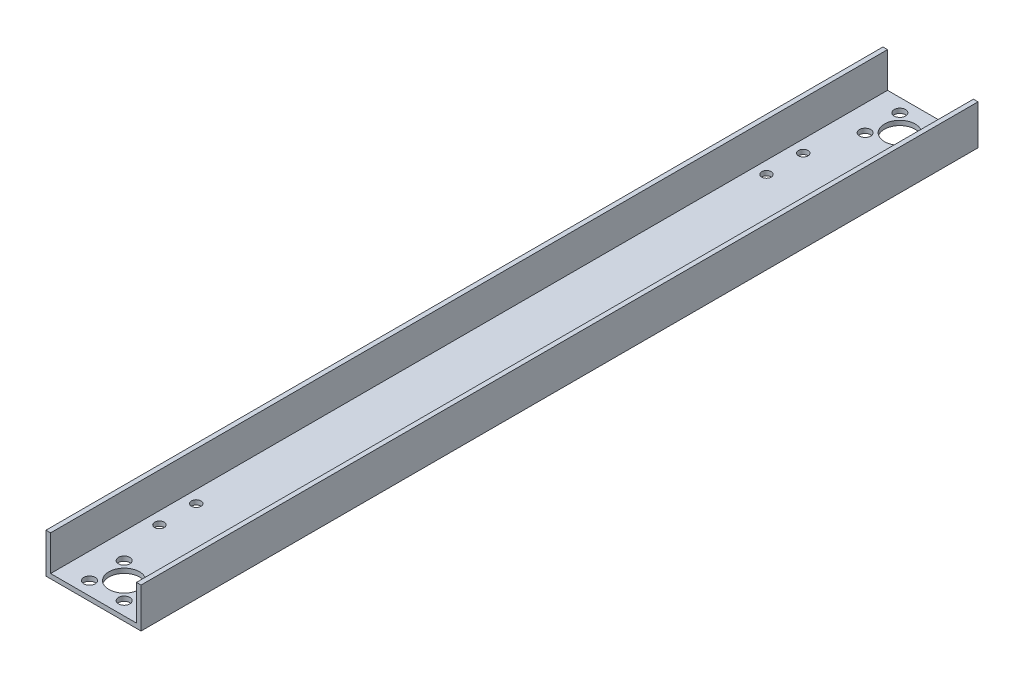
SolidWorks part; units mm, degrees
ref_plane "Front Plane" through (0, 0, 0) normal (0, 0, 1) x (1, 0, 0)
ref_plane "Top Plane" through (0, 0, 0) normal (0, 1, 0) x (1, 0, 0)
ref_plane "Right Plane" through (0, 0, 0) normal (1, 0, 0) x (0, 0, -1)
sketch "Sketch1" plane through (0, 0, 0) normal (0, 0, 1) x (1, 0, 0)
  line L0 (14, 6.5) -> (15.5, 6.5)
  line L1 (-15.5, 6.5) -> (-14, 6.5)
  line L2 (-15.5, 6.5) -> (-15.5, -6.5)
  line L3 (-15.5, -6.5) -> (15.5, -6.5)
  line L4 (15.5, 6.5) -> (15.5, -6.5)
  line L5 (-15.5, 6.5) -> (15.5, -6.5) construction
  line L6 (-15.5, -6.5) -> (15.5, 6.5) construction
  line L8 (-14, 6.5) -> (-14, -5)
  line L9 (-14, -5) -> (14, -5)
  line L10 (14, 6.5) -> (14, -5)
  point P0 (0, 0)
  dimension "D1" = 13
  dimension "D2" = 31
  dimension "D3" = 1.5
  dimension "D4" = 1.5
extrude "Boss-Extrude1" add sketch "Sketch1" along normal blind 273
sketch "Sketch3" plane through (0, -5, 0) normal (0, 1, 0) x (1, 0, 0)
  line L0 (0, 0) -> (0, -273) construction
  line L1 (14, -273) -> (-14, -273) construction
  line L3 (0, -136.5) -> (15.5, -136.5) construction
  line L4 (5.6569, -257.3431) -> (-5.6569, -268.6569) construction
  line L5 (0, -263) -> (0.7501, -263) construction
  line L6 (5.6569, -268.6569) -> (-5.6569, -257.3431) construction
  line L7 (15.5, -273) -> (15.5, 0) construction
  line L8 (5.6569, -4.3431) -> (-5.6569, -15.6569) construction
  line L9 (0, -10) -> (0.7501, -10) construction
  line L10 (5.6569, -15.6569) -> (-5.6569, -4.3431) construction
  circle A0 centre (-5.6569, -4.3431) radius 1.85
  circle A1 centre (0, -263) radius 5
  circle A2 centre (-5.6569, -257.3431) radius 1.85
  circle A3 centre (5.6569, -257.3431) radius 1.85
  circle A4 centre (5.6569, -268.6569) radius 1.85
  circle A5 centre (-5.6569, -268.6569) radius 1.85
  circle A6 centre (5.6569, -4.3431) radius 1.85
  circle A7 centre (5.6569, -15.6569) radius 1.85
  circle A8 centre (-5.6569, -15.6569) radius 1.85
  circle A9 centre (0, -10) radius 5
  dimension "D1" = 10
  dimension "D7" = 3.7
  dimension "D2" = 253
  dimension "D3" = 10
  dimension "D4" = 90
  dimension "D5" = 45
  dimension "D6" = 8
extrude "Cut-Extrude1" cut sketch "Sketch3" against normal blind 273
sketch "Sketch4" plane through (0, -6.5, 0) normal (0, -1, 0) x (1, 0, 0)
  line L0 (0, 10) -> (0, 263) construction
  line L1 (-110, 26.5) -> (110, 26.5) construction
  line L2 (-110, 26.5) -> (-110, 246.5) construction
  line L3 (-110, 246.5) -> (110, 246.5) construction
  line L4 (110, 26.5) -> (110, 246.5) construction
  line L5 (-110, 26.5) -> (110, 246.5) construction
  line L6 (-110, 246.5) -> (110, 26.5) construction
  point P0 (0, 136.5)
  dimension "D1" = 220
sketch "Sketch5" plane through (0, -6.5, 0) normal (0, -1, 0) x (1, 0, 0)
  circle A0 centre (-10, 229.5) radius 1.55
  circle A1 centre (-10, 241.5) radius 1.55
  circle A2 centre (10, 229.5) radius 1.55
  circle A3 centre (10, 241.5) radius 1.55
  circle A4 centre (10, 31.5) radius 1.55
  circle A5 centre (10, 43.5) radius 1.55
  circle A6 centre (-10, 31.5) radius 1.55
  circle A7 centre (-10, 43.5) radius 1.55
extrude "Cut-Extrude2" cut sketch "Sketch5" against normal blind 220
